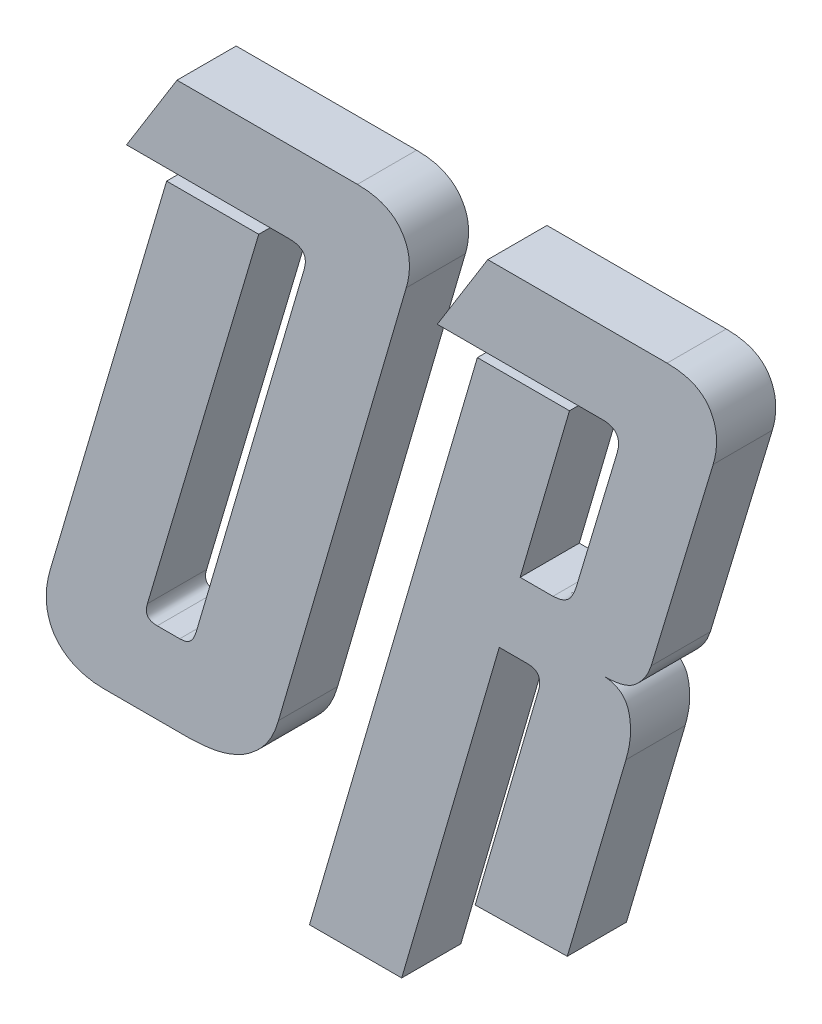
SolidWorks part; units mm, degrees
ref_plane "Plan de face" through (0, 0, 0) normal (0, 0, 1) x (1, 0, 0)
ref_plane "Plan de dessus" through (0, 0, 0) normal (0, 1, 0) x (1, 0, 0)
ref_plane "Plan de droite" through (0, 0, 0) normal (1, 0, 0) x (0, 0, -1)
sketch "Esquisse1" plane through (0, 0, 0) normal (0, 0, 1) x (1, 0, 0)
  line L0 (0, 0) -> (42.566, 0) construction
  text T0 "OR" font "Avengeance Heroic Avenger" height in points 72
extrude "Boss.-Extru.1" add sketch "Esquisse1" along normal blind 2
